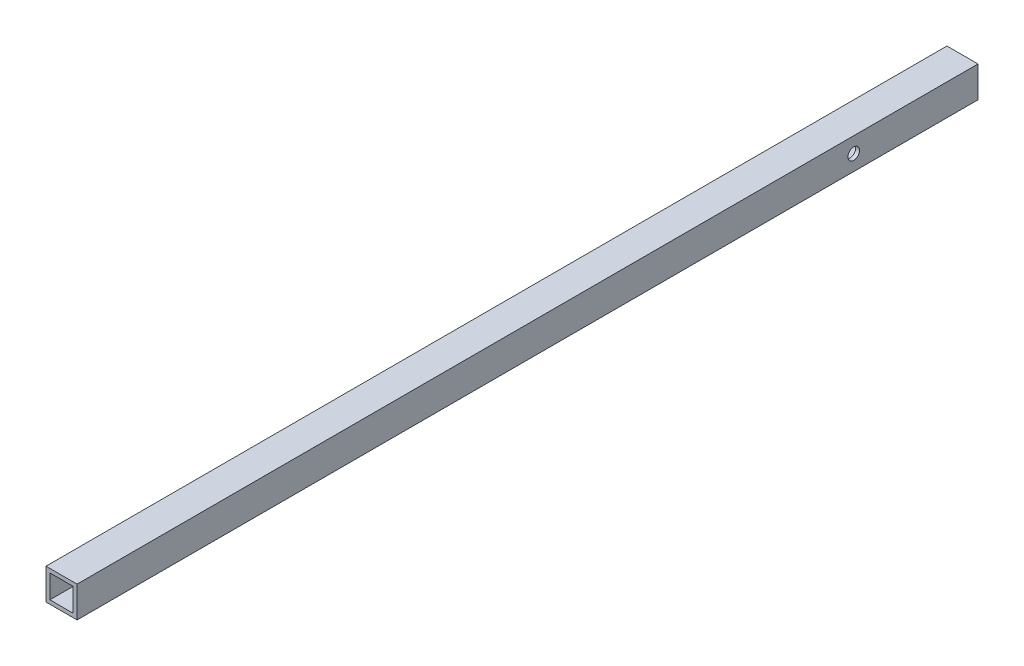
SolidWorks part; units mm, degrees
ref_plane "Front Plane" through (0, 0, 0) normal (0, 0, 1) x (1, 0, 0)
ref_plane "Top Plane" through (0, 0, 0) normal (0, 1, 0) x (1, 0, 0)
ref_plane "Right Plane" through (0, 0, 0) normal (1, 0, 0) x (0, 0, -1)
sketch "Sketch1" plane through (0, 0, 0) normal (0, 0, 1) x (1, 0, 0)
  line L0 (-6.4742, 11.5232) -> (12.5758, 11.5232)
  line L1 (-9.6492, 14.6982) -> (15.7508, 14.6982)
  line L2 (-9.6492, 14.6982) -> (-9.6492, -10.7018)
  line L3 (-9.6492, -10.7018) -> (15.7508, -10.7018)
  line L4 (15.7508, 14.6982) -> (15.7508, -10.7018)
  line L5 (12.5758, 11.5232) -> (12.5758, -7.5268)
  line L6 (-6.4742, -7.5268) -> (12.5758, -7.5268)
  line L7 (-6.4742, 11.5232) -> (-6.4742, -7.5268)
  dimension "D1" = 25.4
  dimension "D2" = 25.4
  dimension "D3" = 3.175
extrude "Boss-Extrude1" add sketch "Sketch1" along normal blind 736.6
sketch "Sketch3" plane through (-9.6492, 0, 0) normal (-1, 0, 0) x (0, 0, 1)
  line L0 (736.6, -10.7018) -> (0, -10.7018) construction
  line L1 (0, 14.6982) -> (0, -10.7018) construction
  circle A0 centre (101.6, 1.9982) radius 4.7625
  dimension "D1" = 12.7
  dimension "D2" = 101.6
extrude "Cut-Extrude1" cut sketch "Sketch3" against normal blind 127
